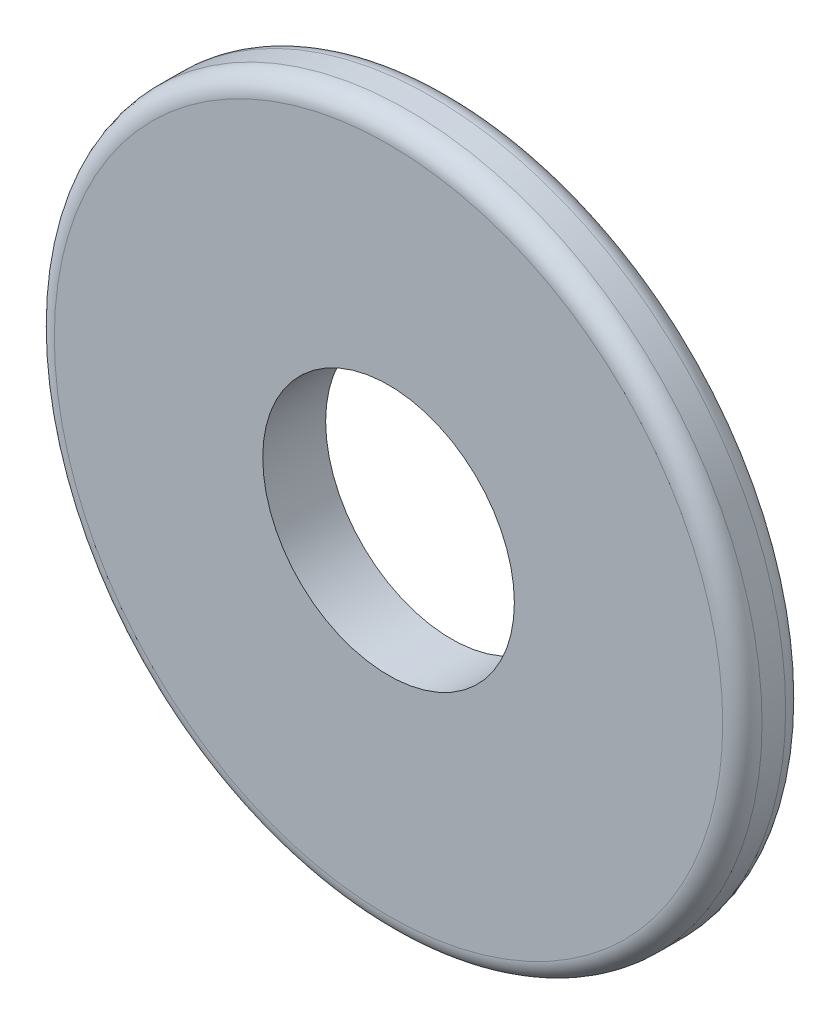
SolidWorks part; units mm, degrees
material "Нержавеющая сталь (ферритная)"
ref_plane "Front" through (0, 0, 0) normal (0, 0, 1) x (1, 0, 0)
ref_plane "Top" through (0, 0, 0) normal (0, 1, 0) x (1, 0, 0)
ref_plane "Right" through (0, 0, 0) normal (1, 0, 0) x (0, 0, -1)
sketch "Эскиз1" plane through (0, 0, 0) normal (0, 0, 1) x (1, 0, 0)
  circle A0 centre (0, 0) radius 9
extrude "Бобышка-Вытянуть1" add sketch "Эскиз1" along normal blind 1.6
sketch "Эскиз2" plane through (0, 0, 1.6) normal (0, 0, 1) x (1, 0, 0)
  circle A0 centre (0, 0) radius 3.2
extrude "Вырез-Вытянуть1" cut sketch "Эскиз2" against normal blind 1.6
fillet "Скругление1" radius 0.5 2 edges at (9, 0, 0) (9, 0, 1.6)
